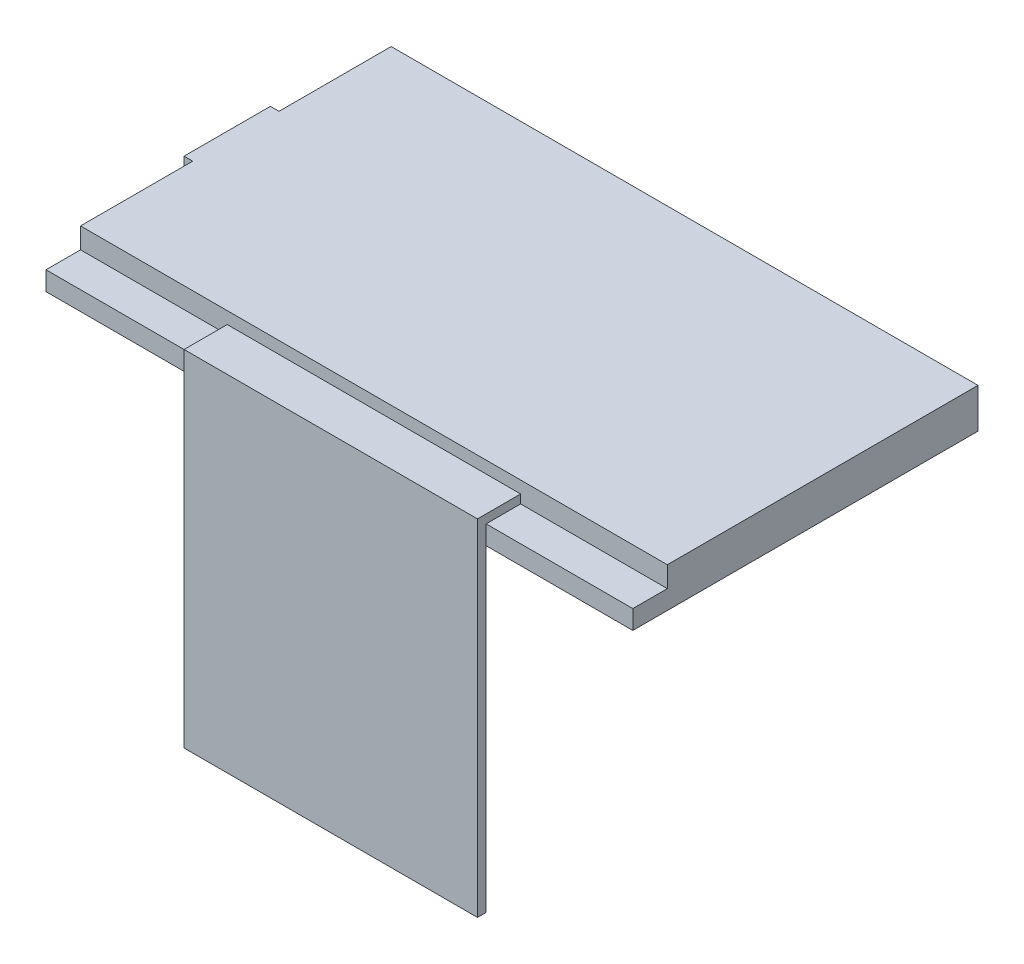
SolidWorks part; units mm, degrees
ref_plane "Front Plane" through (0, 0, 0) normal (0, 0, 1) x (1, 0, 0)
ref_plane "Top Plane" through (0, 0, 0) normal (0, 1, 0) x (1, 0, 0)
ref_plane "Right Plane" through (0, 0, 0) normal (1, 0, 0) x (0, 0, -1)
sketch "Sketch1" plane through (0, 0, 0) normal (0, 1, 0) x (1, 0, 0)
  line L1 (-17, -10) -> (17, -10)
  line L2 (-17, -10) -> (-17, 10)
  line L3 (-17, 10) -> (17, 10)
  line L4 (17, -10) -> (17, 10)
  line L5 (-17, -10) -> (17, 10) construction
  line L6 (-17, 10) -> (17, -10) construction
  point P0 (0, 0)
  dimension "D1" = 34
  dimension "D2" = 20
extrude "Boss-Extrude1" add sketch "Sketch1" along normal blind 1.1
sketch "Sketch3" plane through (0, 1.1, 0) normal (0, 1, 0) x (1, 0, 0)
  line L0 (17, -10) -> (17, 10) construction
  line L1 (-17, 10) -> (17, 10)
  line L2 (-17, 10) -> (-17, -8)
  line L3 (-17, -8) -> (17, -8)
  line L4 (17, 10) -> (17, -8)
  dimension "D1" = 18
extrude "Boss-Extrude2" add sketch "Sketch3" along normal blind 1.2
sketch "Sketch4" plane through (-17, 0, 0) normal (-1, 0, 0) x (0, 0, 1)
  line L0 (-10, 0) -> (10, 0) construction
  line L1 (-3.5, 0) -> (1.5, 0)
  line L2 (-3.5, 0) -> (-3.5, 2.3)
  line L3 (-3.5, 2.3) -> (1.5, 2.3)
  line L4 (1.5, 0) -> (1.5, 2.3)
  line L5 (-10, 2.3) -> (8, 2.3) construction
  point P8 (-1, 2.3)
  point P9 (-1, 2.3)
  dimension "D1" = 5
extrude "Boss-Extrude3" add sketch "Sketch4" along normal blind 0.5
sketch "Sketch5" plane through (0, 1.1, 0) normal (0, 1, 0) x (1, 0, 0)
  line L0 (-17, -10) -> (17, -10) construction
  line L1 (-8.5, -10) -> (8.5, -10)
  line L2 (-8.5, -10) -> (-8.5, -8)
  line L3 (-8.5, -8) -> (8.5, -8)
  line L4 (8.5, -10) -> (8.5, -8)
  line L5 (-17, -8) -> (17, -8) construction
  point P8 (0, -10)
  point P9 (0, -10)
  dimension "D1" = 17
extrude "Boss-Extrude4" add sketch "Sketch5" along normal blind 0.5
sketch "Sketch6" plane through (0, 1.6, 0) normal (0, 1, 0) x (1, 0, 0)
  line L1 (-8.5, -10) -> (8.5, -10)
  line L2 (-8.5, -10) -> (-8.5, -10.5)
  line L3 (-8.5, -10.5) -> (8.5, -10.5)
  line L4 (8.5, -10) -> (8.5, -10.5)
  point P5 (8.0685, -10)
  dimension "D1" = 0.5
extrude "Boss-Extrude5" add sketch "Sketch6" against normal blind 20
